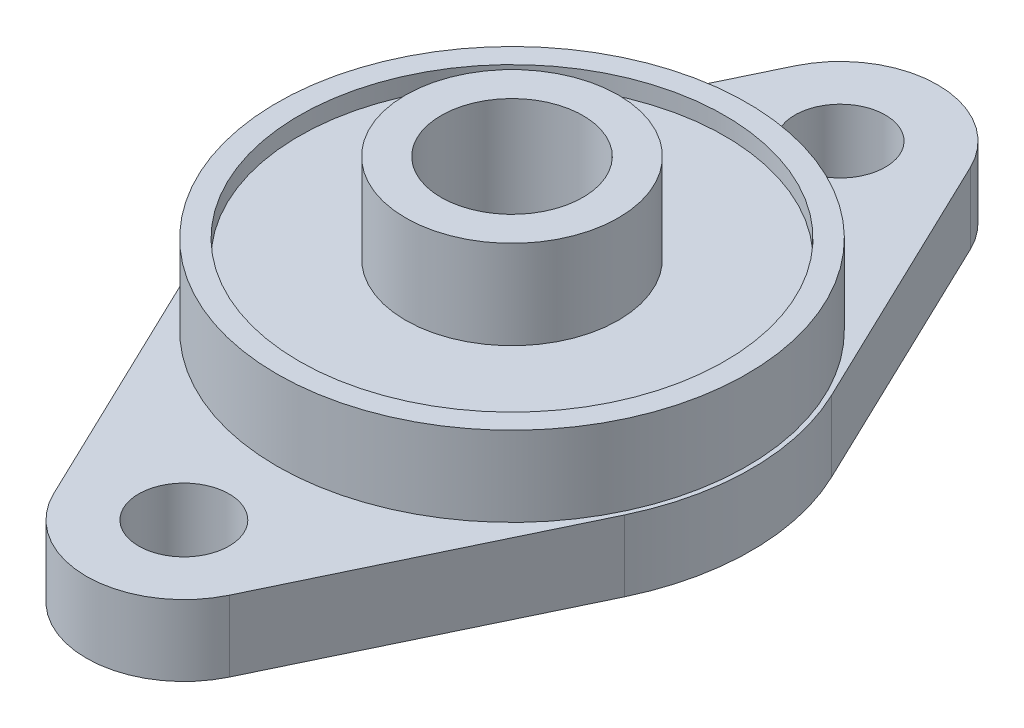
SolidWorks part; units mm, degrees
ref_plane "Front Plane" through (0, 0, 0) normal (0, 0, 1) x (1, 0, 0)
ref_plane "Top Plane" through (0, 0, 0) normal (0, 1, 0) x (1, 0, 0)
ref_plane "Right Plane" through (0, 0, 0) normal (1, 0, 0) x (0, 0, -1)
sketch "Sketch1" plane through (0, 0, 0) normal (0, 1, 0) x (1, 0, 0)
  line L0 (0, -18.5) -> (0, 18.5) construction
  line L5 (4.9592, 20.8784) -> (12.1725, 5.8378)
  line L6 (-4.9592, 20.8784) -> (-12.1725, 5.8378)
  line L7 (12.1725, -5.8378) -> (4.9592, -20.8784)
  line L8 (-12.1725, -5.8378) -> (-4.9592, -20.8784)
  circle A1 centre (0, 18.5) radius 2.55
  circle A2 centre (0, -18.5) radius 2.55
  arc A7 (4.9592, 20.8784) -> (-4.9592, 20.8784) centre (0, 18.5) ccw
  arc A8 (-4.9592, -20.8784) -> (4.9592, -20.8784) centre (0, -18.5) ccw
  arc A9 (-12.1725, 5.8378) -> (-12.1725, -5.8378) centre (0, 0) ccw
  arc A11 (12.1725, -5.8378) -> (12.1725, 5.8378) centre (0, 0) ccw
  point P6 (0, 0)
  dimension "D3" = 5.1
  dimension "D4" = 5.1
  dimension "D5" = 11
  dimension "D6" = 11
  dimension "D2" = 37
extrude "Boss-Extrude1" add sketch "Sketch1" along normal blind 4
sketch "Sketch2" plane through (0, 4, 0) normal (0, 1, 0) x (1, 0, 0)
  circle A0 centre (0, 0) radius 13.25
  dimension "D1" = 26.5
extrude "Boss-Extrude2" add sketch "Sketch2" along normal blind 4.5
sketch "Sketch3" plane through (0, 8.5, 0) normal (0, 1, 0) x (1, 0, 0)
  circle A0 centre (0, 0) radius 12
  dimension "D1" = 24
extrude "Cut-Extrude1" cut sketch "Sketch3" against normal blind 1
sketch "Sketch4" plane through (0, 7.5, 0) normal (0, 1, 0) x (1, 0, 0)
  circle A0 centre (0, 0) radius 6
  dimension "D1" = 12
extrude "Boss-Extrude3" add sketch "Sketch4" along normal blind 5
sketch "Sketch5" plane through (0, 12.5, 0) normal (0, 1, 0) x (1, 0, 0)
  circle A0 centre (0, 0) radius 4
  dimension "D1" = 8
extrude "Cut-Extrude2" cut sketch "Sketch5" against normal through all
